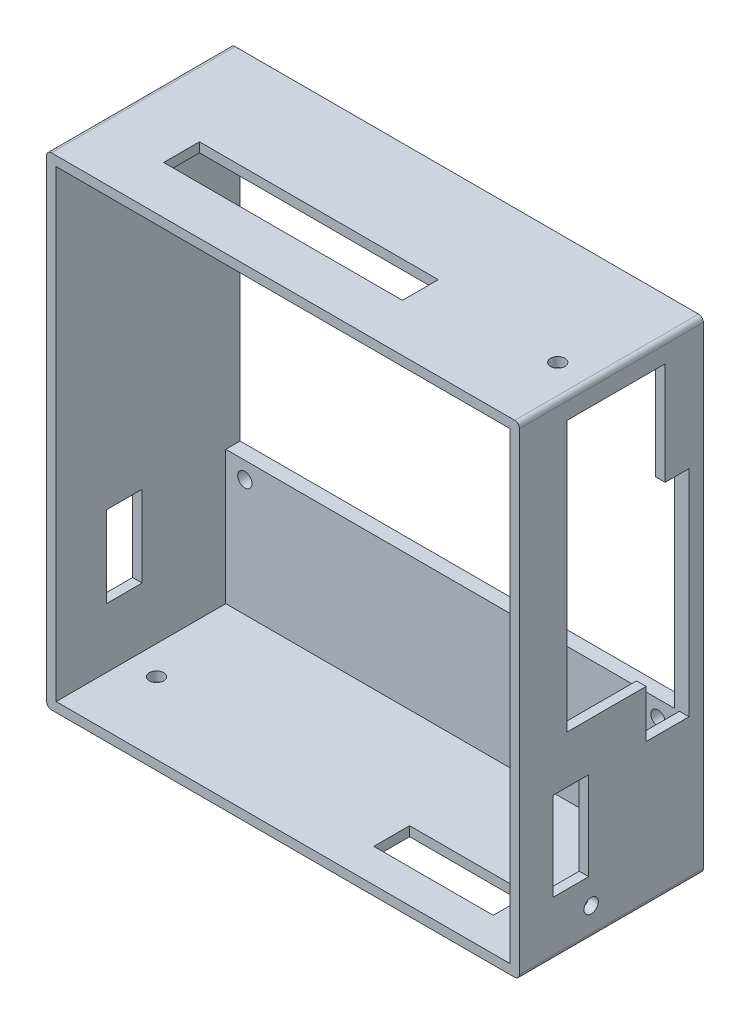
SolidWorks part; units mm, degrees
ref_plane "前视基准面" through (0, 0, 0) normal (0, 0, 1) x (1, 0, 0)
ref_plane "上视基准面" through (0, 0, 0) normal (0, 1, 0) x (1, 0, 0)
ref_plane "右视基准面" through (0, 0, 0) normal (1, 0, 0) x (0, 0, -1)
sketch "草图1" plane through (0, 0, 0) normal (0, 0, 1) x (1, 0, 0)
  line L1 (-47.5, -30.5) -> (47.5, -30.5)
  line L2 (-47.5, -30.5) -> (-47.5, 30.5)
  line L3 (-47.5, 30.5) -> (47.5, 30.5)
  line L4 (47.5, -30.5) -> (47.5, 30.5)
  line L5 (-47.5, -30.5) -> (47.5, 30.5) construction
  line L6 (-47.5, 30.5) -> (47.5, -30.5) construction
  line L10 (-49.5, 40.5) -> (49.5, 40.5)
  line L11 (49.5, 40.5) -> (49.5, -63.5)
  line L12 (49.5, -63.5) -> (-49.5, -63.5)
  line L13 (-49.5, -63.5) -> (-49.5, 40.5)
  circle A0 centre (43, 34) radius 1.5
  circle A1 centre (-43.5, 34) radius 1.5
  circle A2 centre (-43.5, -34) radius 1.5
  circle A3 centre (43, -34) radius 1.5
  point P0 (0, 0)
extrude "凸台-拉伸3" add sketch "草图1" along normal blind 3
sketch "草图3" plane through (0, 0, 3) normal (0, 0, 1) x (1, 0, 0)
  line L0 (-47.5, 38.5) -> (-47.5, -61.5)
  line L1 (-47.5, -61.5) -> (47.5, -61.5)
  line L2 (47.5, -61.5) -> (47.5, 38.5)
  line L3 (47.5, 38.5) -> (-47.5, 38.5)
  line L4 (-49.5, 40.5) -> (-49.5, -63.5)
  line L5 (-49.5, -63.5) -> (49.5, -63.5)
  line L6 (49.5, -63.5) -> (49.5, 40.5)
  line L7 (49.5, 40.5) -> (-49.5, 40.5)
  line L8 (-49.5, 40.5) -> (-49.5, -63.5)
  line L9 (-49.5, -63.5) -> (49.5, -63.5)
  line L10 (49.5, -63.5) -> (49.5, 40.5)
  line L11 (49.5, 40.5) -> (-49.5, 40.5)
  dimension "D1" = 0
  dimension "D2" = 2
extrude "凸台-拉伸4" add sketch "草图3" along normal blind 33
sketch "草图4" plane through (47.5, 0, 0) normal (-1, 0, 0) x (0, 0, 1)
  line L2 (12, 14.5) -> (12, -30.5)
  line L3 (12, -30.5) -> (3, -30.5)
  line L5 (0, 14.5) -> (0, -30.5)
  line L6 (0, -30.5) -> (3, -30.5)
  line L7 (12, 14.5) -> (0, 14.5)
extrude "切除-拉伸2" cut sketch "草图4" against normal blind 30
sketch "草图5" plane through (0, 40.5, 0) normal (0, 1, 0) x (1, 0, 0)
  line L0 (15, -28.5) -> (-35, -28.5)
  line L2 (-35, -21) -> (15, -21)
  line L3 (-35, -28.5) -> (-35, -21)
  line L4 (15, -21) -> (15, -28.5)
extrude "切除-拉伸3" cut sketch "草图5" against normal blind 30
sketch "草图6" plane through (47.5, 0, 0) normal (-1, 0, 0) x (0, 0, 1)
  line L0 (36, 38.5) -> (36, -16.5)
  line L1 (36, -61.5) -> (36, 38.5) construction
  line L2 (36, 38.5) -> (3, 38.5) construction
  line L3 (36, -16.5) -> (8, -16.5)
  line L4 (8, -16.5) -> (8, 38.5)
  line L5 (8, 38.5) -> (36, 38.5)
extrude "切除-拉伸4" cut sketch "草图6" against normal blind 30
sketch "草图7" plane through (47.5, 0, 0) normal (-1, 0, 0) x (0, 0, 1)
  line L1 (24, -30.5) -> (24, -49)
  line L5 (24, -30.5) -> (31.5, -30.5)
  line L6 (31.5, -30.5) -> (31.5, -49)
  line L7 (31.5, -49) -> (24, -49)
extrude "切除-拉伸5" cut sketch "草图7" against normal blind 30
sketch "草图8" plane through (0, -61.5, 0) normal (0, 1, 0) x (1, 0, 0)
  line L2 (40, -28.5) -> (15, -28.5)
  line L3 (15, -28.5) -> (15, -21)
  line L4 (15, -21) -> (40, -21)
  line L5 (40, -21) -> (40, -28.5)
extrude "切除-拉伸6" cut sketch "草图8" against normal blind 30
fillet "圆角1" radius 1 4 edges at (-49.5, 40.5, 18) (49.5, 40.5, 18) (49.5, -63.5, 18) (-49.5, -63.5, 18)
sketch "草图9" plane through (0, 0, 36) normal (0, 0, 1) x (1, 0, 0)
  line L0 (47.5, -16.5) -> (47.5, 38.5)
  line L1 (49.5, 38.5) -> (-47.5, 38.5) construction
  line L2 (47.5, 38.5) -> (49.5, 38.5)
  line L3 (49.5, 38.5) -> (49.5, -16.5)
  line L4 (49.5, -16.5) -> (47.5, -16.5)
extrude "凸台-拉伸5" add sketch "草图9" against normal blind 7.5
sketch "草图14" plane through (0, -61.5, 0) normal (0, 1, 0) x (1, 0, 0)
  line L0 (40, -28.5) -> (40, -21) construction
  line L1 (40, -21) -> (15, -21) construction
  line L2 (15, -28.5) -> (40, -28.5) construction
  line L3 (15, -21) -> (15, -28.5) construction
  line L4 (47.5, -3) -> (-47.5, -3)
  line L5 (-47.5, -3) -> (-47.5, -36)
  line L6 (-47.5, -36) -> (47.5, -36)
  line L7 (47.5, -36) -> (47.5, -3)
  line L8 (47.5, -3) -> (-47.5, -3)
  line L9 (-47.5, -3) -> (-47.5, -36)
  line L10 (-47.5, -36) -> (47.5, -36)
  line L11 (47.5, -36) -> (47.5, -3)
  line L12 (40, -28.5) -> (40, -21)
  line L13 (40, -21) -> (15, -21)
  line L14 (15, -28.5) -> (40, -28.5)
  line L15 (15, -21) -> (15, -28.5)
  dimension "D1" = 0
extrude "凸台-拉伸6" add sketch "草图14" along normal blind 3
sketch "草图15" plane through (0, -63.5, 0) normal (0, -1, 0) x (1, 0, 0)
  line L1 (92.1466, -51.2955) -> (-86.0456, -51.2955)
  line L2 (92.1466, -51.2955) -> (92.1466, 83.0993)
  line L3 (92.1466, 83.0993) -> (-86.0456, 83.0993)
  line L4 (-86.0456, -51.2955) -> (-86.0456, 83.0993)
  line L5 (92.1466, -51.2955) -> (-86.0456, 83.0993) construction
  line L6 (92.1466, 83.0993) -> (-86.0456, -51.2955) construction
  point P0 (3.0505, 15.9019)
extrude "切除-拉伸8" cut sketch "草图15" against normal blind 3
sketch "草图16" plane through (0, 0, 0) normal (0, 0, -1) x (-1, 0, 0)
  line L1 (-47.5, 30.5) -> (-46.5, 30.5)
  line L2 (-47.5, 30.5) -> (47.5, 30.5) construction
  line L3 (-46.5, 30.5) -> (-46.5, -30.5)
  line L4 (47.5, -30.5) -> (-49.5, -30.5) construction
  line L5 (-46.5, -30.5) -> (-49.5, -30.5)
  line L6 (-49.5, -30.5) -> (-49.5, 14.5)
  line L7 (-47.5, 30.5) -> (-47.5, 14.5)
  line L8 (-47.5, 14.5) -> (-49.5, 14.5)
extrude "凸台-拉伸7" add sketch "草图16" against normal blind 3
sketch "草图17" plane through (-49.5, 0, 0) normal (-1, 0, 0) x (0, 0, 1)
  line L11 (28, -46) -> (28, -29)
  line L17 (20.5, -46) -> (28, -46)
  line L18 (20.5, -46) -> (20.5, -29)
  line L19 (20.5, -29) -> (28, -29)
extrude "切除-拉伸9" cut sketch "草图17" against normal blind 3
fillet "圆角3" radius 1 2 edges at (-49.5, -60.5, 18) (49.5, -60.5, 18)
sketch "草图19" plane through (0, 0, 36) normal (0, 0, 1) x (1, 0, 0)
  line L4 (47.5, -58.5) -> (47.5, 38.5)
  line L5 (-47.5, -58.5) -> (47.5, -58.5)
  line L6 (-47.5, 38.5) -> (-47.5, -58.5)
  line L7 (47.5, 38.5) -> (-47.5, 38.5)
  line L8 (47.5, -58.5) -> (47.5, 38.5)
  line L9 (-47.5, -58.5) -> (47.5, -58.5)
  line L10 (-47.5, 38.5) -> (-47.5, -58.5)
  line L11 (47.5, 38.5) -> (-47.5, 38.5)
  line L12 (-49.5, 39.5) -> (-49.5, -59.5)
  line L13 (-48.5, -60.5) -> (48.5, -60.5)
  line L14 (49.5, -59.5) -> (49.5, 39.5)
  line L15 (48.5, 40.5) -> (-48.5, 40.5)
  line L16 (-49.5, 39.5) -> (-49.5, -59.5)
  line L17 (-48.5, -60.5) -> (48.5, -60.5)
  line L18 (49.5, -59.5) -> (49.5, 39.5)
  line L19 (48.5, 40.5) -> (-48.5, 40.5)
  arc A4 (-49.5, -59.5) -> (-48.5, -60.5) centre (-48.5, -59.5) ccw
  arc A5 (48.5, -60.5) -> (49.5, -59.5) centre (48.5, -59.5) ccw
  arc A6 (49.5, 39.5) -> (48.5, 40.5) centre (48.5, 39.5) ccw
  arc A7 (-48.5, 40.5) -> (-49.5, 39.5) centre (-48.5, 39.5) ccw
  arc A8 (-49.5, -59.5) -> (-48.5, -60.5) centre (-48.5, -59.5) ccw
  arc A9 (48.5, -60.5) -> (49.5, -59.5) centre (48.5, -59.5) ccw
  arc A10 (49.5, 39.5) -> (48.5, 40.5) centre (48.5, 39.5) ccw
  arc A11 (-48.5, 40.5) -> (-49.5, 39.5) centre (-48.5, 39.5) ccw
  dimension "D1" = 0
  dimension "D2" = 0
extrude "凸台-拉伸8" add sketch "草图19" along normal blind 2.5
sketch "草图20" plane through (0, 38.5, 0) normal (0, -1, 0) x (1, 0, 0)
  line L1 (47.5, 8) -> (49.5, 8)
  line L2 (47.5, 8) -> (47.5, 28.5)
  line L3 (47.5, 28.5) -> (49.5, 28.5)
  line L4 (49.5, 8) -> (49.5, 28.5)
extrude "凸台-拉伸9" add sketch "草图20" along normal blind 2.5
sketch "草图21" plane through (0, -60.5, 0) normal (0, -1, 0) x (1, 0, 0)
  line L0 (15, 21) -> (15, 28.5) construction
  line L4 (15, 21) -> (15, 28.5)
  line L10 (43, 31.5) -> (18, 31.5)
  line L12 (43, 31.5) -> (43, 24)
  line L13 (43, 24) -> (18, 24)
  line L14 (18, 24) -> (18, 31.5)
  line M10 (15, 28.5) -> (40, 28.5)
  line M11 (40, 28.5) -> (40, 21)
extrude "切除-拉伸10" cut sketch "草图21" against normal blind 2 contours L14 L13 L12 L10 M10 M11
sketch "草图23" plane through (0, -60.5, 0) normal (0, -1, 0) x (1, 0, 0)
  line L0 (15, 28.5) -> (18, 28.5) construction
  line L1 (15, 21) -> (15, 28.5) construction
  line L2 (40, 21) -> (15, 21) construction
  line L3 (40, 24) -> (40, 21) construction
  line L4 (15, 28.5) -> (18, 28.5)
  line L5 (15, 21) -> (15, 28.5)
  line L6 (40, 21) -> (15, 21)
  line L7 (40, 24) -> (40, 21)
  line L8 (40, 24) -> (18, 24)
  line L9 (18, 24) -> (18, 28.5)
extrude "凸台-拉伸11" add sketch "草图23" against normal blind 2
sketch "草图24" plane through (49.5, 0, 0) normal (1, 0, 0) x (0, 0, -1)
  circle A0 centre (-23.5, -54.5) radius 1.5
extrude "切除-拉伸11" cut sketch "草图24" against normal blind 2
sketch "草图25" plane through (0, -60.5, 0) normal (0, -1, 0) x (1, 0, 0)
  circle A1 centre (-41.5, 23.5) radius 1.5
extrude "切除-拉伸12" cut sketch "草图25" against normal blind 2
sketch "草图26" plane through (-49.5, 0, 0) normal (-1, 0, 0) x (0, 0, 1)
  circle A0 centre (23.5, 33.5) radius 1.5
extrude "切除-拉伸13" cut sketch "草图26" against normal blind 2
sketch "草图27" plane through (0, 40.5, 0) normal (0, 1, 0) x (1, 0, 0)
  circle A1 centre (42.5, -23.5) radius 1.5
extrude "切除-拉伸14" cut sketch "草图27" against normal blind 2
sketch "草图28" plane through (0, -16.5, 0) normal (0, 1, 0) x (1, 0, 0)
  line L4 (47.5, -12) -> (47.5, -28.5)
  line L5 (47.5, -28.5) -> (49.5, -28.5)
  line L6 (49.5, -28.5) -> (49.5, -12)
  line L7 (49.5, -12) -> (47.5, -12)
  line L8 (47.5, -12) -> (47.5, -28.5)
  line L9 (47.5, -28.5) -> (49.5, -28.5)
  line L10 (49.5, -28.5) -> (49.5, -12)
  line L11 (49.5, -12) -> (47.5, -12)
  dimension "D1" = 0
extrude "切除-拉伸15" cut sketch "草图28" against normal blind 4
sketch "草图29" plane through (0, -60.5, 0) normal (0, -1, 0) x (1, 0, 0)
  line L0 (43, 24) -> (37, 24)
  line L1 (43, 24) -> (18, 24) construction
  line L2 (37, 24) -> (37, 31.5)
  line L3 (43, 31.5) -> (18, 31.5) construction
  line L4 (37, 31.5) -> (43, 31.5)
  line L5 (43, 31.5) -> (43, 24)
extrude "凸台-拉伸12" add sketch "草图29" against normal blind 2
sketch "草图30" plane through (0, -60.5, 0) normal (0, -1, 0) x (1, 0, 0)
  line L0 (18, 24) -> (12, 24)
  line L1 (18, 24) -> (18, 31.5)
  line L2 (18, 31.5) -> (12, 31.5)
  line L3 (12, 31.5) -> (12, 24)
extrude "切除-拉伸16" cut sketch "草图30" against normal blind 2
